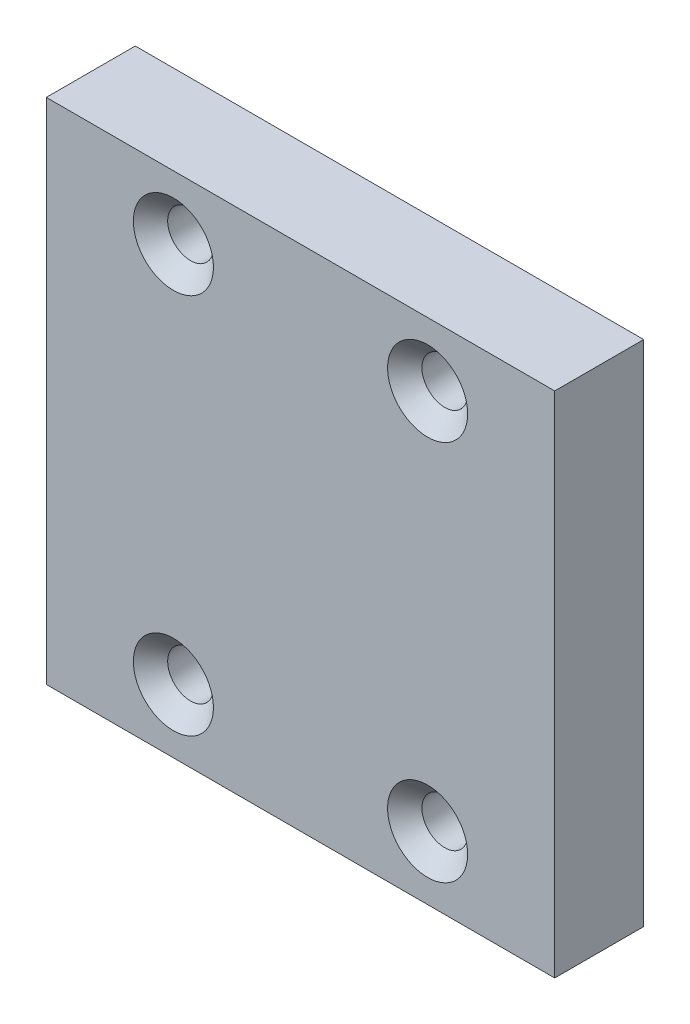
SolidWorks part; units mm, degrees
ref_plane "Piano frontale" through (0, 0, 0) normal (0, 0, 1) x (1, 0, 0)
ref_plane "Piano superiore" through (0, 0, 0) normal (0, 1, 0) x (1, 0, 0)
ref_plane "Piano destro" through (0, 0, 0) normal (1, 0, 0) x (0, 0, -1)
sketch "Schizzo1" plane through (0, 0, 0) normal (0, 0, 1) x (1, 0, 0)
  line L1 (20, -20) -> (-20, -20)
  line L2 (20, -20) -> (20, 20)
  line L3 (20, 20) -> (-20, 20)
  line L4 (-20, -20) -> (-20, 20)
  line L5 (20, -20) -> (-20, 20) construction
  line L6 (20, 20) -> (-20, -20) construction
  point P0 (0, 0)
  dimension "D1" = 40
  dimension "D2" = 40
extrude "Estrusione-Estrusione1" add sketch "Schizzo1" along normal blind 7
sketch "Schizzo2" plane through (0, 0, 7) normal (0, 0, 1) x (1, 0, 0)
  line L0 (-20, 20) -> (-20, 15) construction
  line L1 (-20, 20) -> (-20, -20) construction
  line L2 (-20, 15) -> (-10, 15) construction
  dimension "D1" = 5
  dimension "D2" = 10
hole_wizard "Foro svasato per Vite M3-1" positions "Schizzo3D1" profile "Schizzo4" countersink size "M3" standard "ISO"
sketch3d "Schizzo3D1"
  point P0 (-10, 15, 7)
sketch "Schizzo4" plane through (-10, 15, 7) normal (1, 0, 0) x (0, -1, 0)
  line L0 (0, 0) -> (0, 11.0815)
  line L1 (0, 11.0815) -> (1.8, 10)
  line L2 (1.8, 10) -> (1.8, 1.35)
  line L3 (1.8, 1.35) -> (3.15, 0)
  line L5 (3.15, 0) -> (0, 0)
  line L6 (-1.8, 1.35) -> (-3.15, 0) construction
  line L10 (0, 11.0815) -> (-1.8, 10) construction
  line L11 (0, -6.35) -> (0, 107.95) construction
  dimension "Hole Dia." = 3.6
  dimension "Hole Depth" = 10
  dimension "Near C'Sink Dia." = 6.3
  dimension "Near C'Sink Angle" = 90
  dimension "Drill Angle" = 118
pattern_linear "Ripetizione a L1" count 2 spacing 20 along (1, 0, 0) count 2 spacing 30 along (0, -1, 0) of "Foro svasato per Vite M3-1"
